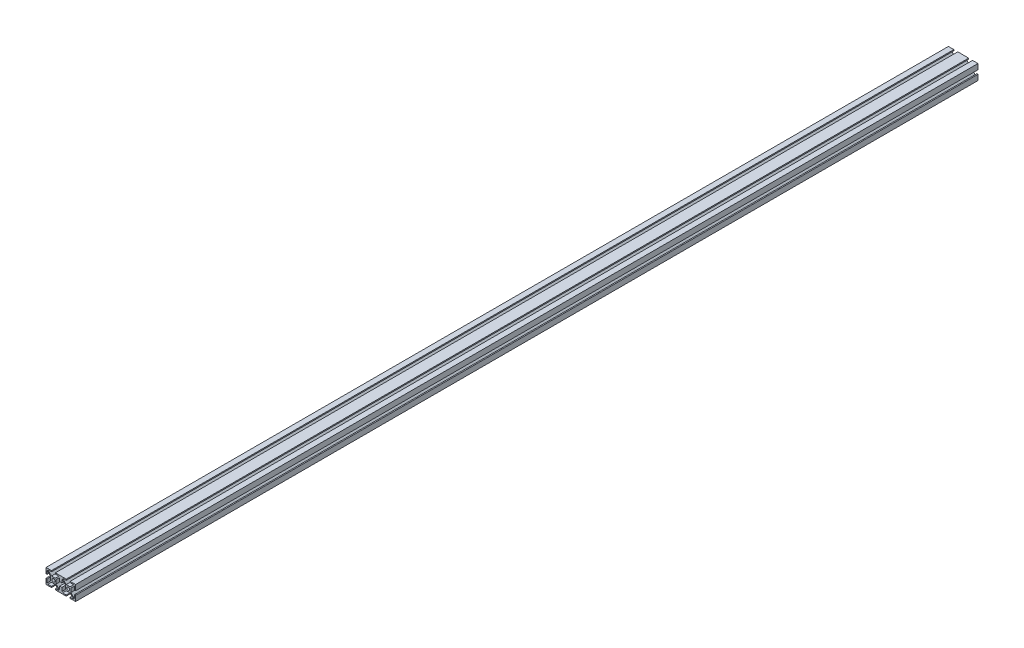
SolidWorks part; units mm, degrees
material "6063-T5"
ref_plane "Front Plane" through (0, 0, 0) normal (0, 0, 1) x (1, 0, 0)
ref_plane "Top Plane" through (0, 0, 0) normal (0, 1, 0) x (1, 0, 0)
ref_plane "Right Plane" through (0, 0, 0) normal (1, 0, 0) x (0, 0, -1)
sketch "Sketch1" plane through (0, 0, 0) normal (0, 0, 1) x (1, 0, 0)
  line L0 (0, 20) -> (20, 0) construction
  line L1 (0, 0) -> (20, 0) construction
  line L2 (0, 0) -> (0, 20) construction
  line L3 (0, 20) -> (20, 20) construction
  line L4 (20, 0) -> (20, 20) construction
  line L5 (20, 20) -> (0, 0) construction
  line L6 (18.5, 1.5) -> (18.5, 0) construction
  line L7 (1.5, 1.5) -> (18.5, 1.5) construction
  line L8 (1.5, 1.5) -> (1.5, 18.5) construction
  line L9 (1.5, 18.5) -> (18.5, 18.5) construction
  line L10 (18.5, 1.5) -> (18.5, 18.5) construction
  line L11 (18.5, 1.5) -> (20, 1.5) construction
  line L12 (6.345, 12.5943) -> (1.5, 17.4393)
  line L13 (13.655, 6.345) -> (6.345, 6.345) construction
  line L14 (13.655, 6.345) -> (13.655, 13.655) construction
  line L15 (13.655, 13.655) -> (6.345, 13.655) construction
  line L16 (6.345, 6.345) -> (6.345, 13.655) construction
  line L17 (7.4057, 13.655) -> (2.5607, 18.5)
  line L18 (2.5607, 18.5) -> (2.0303, 17.9697) construction
  line L19 (2.0303, 17.9697) -> (1.5, 17.4393) construction
  line L20 (6.345, 7.4057) -> (6.345, 12.5943)
  line L21 (12.5943, 13.655) -> (17.4393, 18.5)
  line L22 (17.4393, 18.5) -> (17.9697, 17.9697) construction
  line L23 (17.9697, 17.9697) -> (18.5, 17.4393) construction
  line L24 (18.5, 17.4393) -> (13.655, 12.5943)
  line L25 (13.655, 7.4057) -> (18.5, 2.5607)
  line L26 (18.5, 2.5607) -> (17.9697, 2.0303) construction
  line L27 (17.4393, 1.5) -> (12.5943, 6.345)
  line L28 (7.4057, 6.345) -> (2.5607, 1.5)
  line L29 (17.9697, 2.0303) -> (17.4393, 1.5) construction
  line L30 (1.5, 2.5607) -> (6.345, 7.4057)
  line L31 (2.5607, 1.5) -> (2.0303, 2.0303) construction
  line L32 (2.0303, 2.0303) -> (1.5, 2.5607) construction
  line L33 (7.4057, 13.655) -> (12.5943, 13.655)
  line L34 (13.655, 12.5943) -> (13.655, 7.4057)
  line L36 (12.5943, 6.345) -> (7.4057, 6.345)
  line L37 (0, 10) -> (1.5, 10) construction
  line L38 (0.75, 12.63) -> (0.75, 10) construction
  line L39 (0.75, 10) -> (0.75, 7.37) construction
  line L40 (1.5, 12.63) -> (0, 12.63)
  line L41 (1.5, 7.37) -> (0, 7.37)
  line L42 (10, 1.5) -> (10, 0) construction
  line L43 (10, 0.75) -> (12.63, 0.75) construction
  line L44 (10, 0.75) -> (7.37, 0.75) construction
  line L45 (12.63, 0) -> (12.63, 1.5)
  line L46 (7.37, 1.5) -> (7.37, 0)
  line L47 (18.5, 12.63) -> (20, 12.63)
  line L48 (18.5, 7.37) -> (20, 7.37)
  line L49 (7.37, 20) -> (7.37, 18.5)
  line L50 (12.63, 20) -> (12.63, 18.5)
  line L51 (2.5607, 1.5) -> (7.37, 1.5)
  line L52 (12.63, 1.5) -> (17.4393, 1.5)
  line L53 (18.5, 7.37) -> (18.5, 2.5607)
  line L54 (18.5, 12.63) -> (18.5, 17.4393)
  line L55 (17.4393, 18.5) -> (12.63, 18.5)
  line L56 (7.37, 18.5) -> (2.5607, 18.5)
  line L57 (1.5, 17.4393) -> (1.5, 12.63)
  line L58 (1.5, 7.37) -> (1.5, 2.5607)
  line L59 (7.37, 0) -> (0, 0)
  line L60 (0, 0) -> (0, 7.37)
  line L61 (0, 12.63) -> (0, 20)
  line L62 (0, 20) -> (7.37, 20)
  line L63 (12.63, 20) -> (20, 20)
  line L64 (20, 20) -> (20, 12.63)
  line L65 (20, 7.37) -> (20, 0)
  line L66 (20, 0) -> (12.63, 0)
  circle A0 centre (10, 10) radius 2.095
  dimension "D2" = 4.19
  dimension "D6" = 5.26
  dimension "D1" = 20
  dimension "D3" = 1.5
  dimension "D4" = 3.655
  dimension "D5" = 1.5
extrude "Boss-Extrude1" add sketch "Sketch1" along normal blind 1220
pattern_linear "LPattern1" count 2 spacing 20 along (1, 0, 0) of "Boss-Extrude1"
